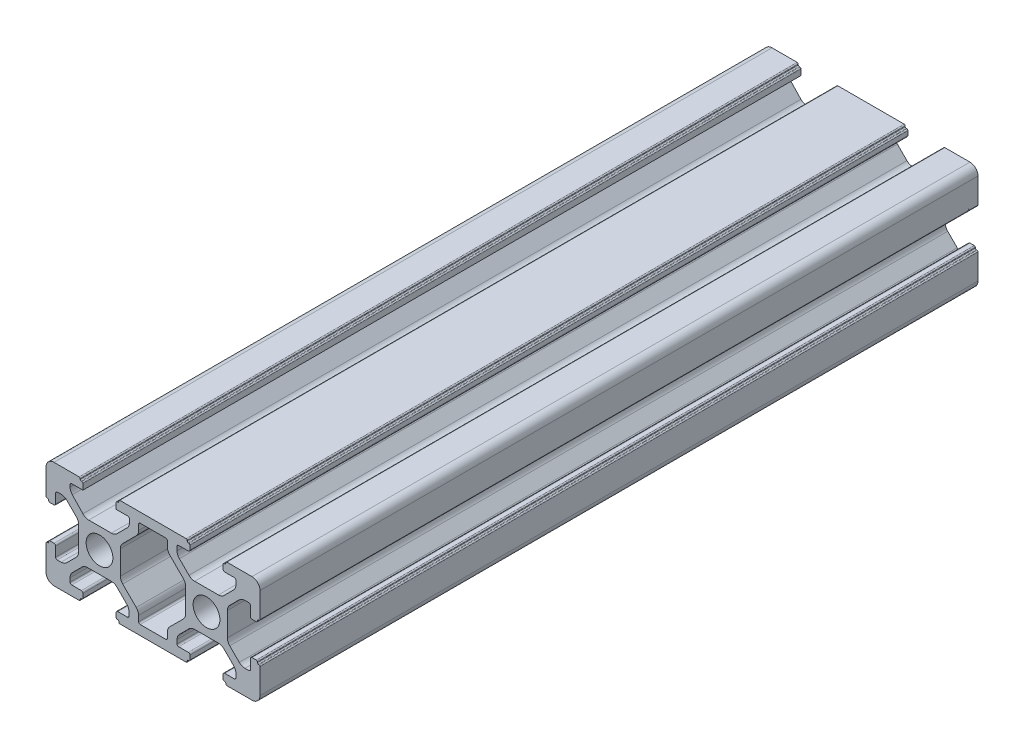
SolidWorks part; units mm, degrees
material "6063-O"
ref_plane "Front Plane" through (0, 0, 0) normal (0, 0, 1) x (1, 0, 0)
ref_plane "Top Plane" through (0, 0, 0) normal (0, 1, 0) x (1, 0, 0)
ref_plane "Right Plane" through (0, 0, 0) normal (1, 0, 0) x (0, 0, -1)
sketch "Sketch1" plane through (0, 0, 0) normal (0, 0, 1) x (1, 0, 0)
  line L0 (1.5, 0) -> (6.2, 0)
  line L1 (40, 1.5) -> (40, 6.2)
  line L2 (38.5, 20) -> (33.8, 20)
  line L3 (0, 18.5) -> (0, 13.8)
  line L4 (17.6, 1.8) -> (22.4, 1.8)
  line L5 (32.218, 13.9) -> (27.782, 13.9)
  line L6 (26.1, 12.218) -> (26.1, 7.782)
  line L7 (17.6, 18.2) -> (22.4, 18.2)
  line L8 (12.218, 13.9) -> (7.9864, 13.9)
  line L9 (6.1, 12.218) -> (6.1, 7.782)
  line L10 (7.782, 6.1) -> (12.218, 6.1)
  line L11 (13.9, 7.782) -> (13.9, 12.218)
  line L12 (27.782, 6.1) -> (32.218, 6.1)
  line L13 (33.9, 7.782) -> (33.9, 12.218)
  line L14 (26.7213, 14.3393) -> (24.9393, 16.1213)
  line L15 (33.2787, 14.3393) -> (35.0607, 16.1213)
  line L16 (34.3393, 13.2787) -> (36.1213, 15.0607)
  line L17 (25.6607, 6.7213) -> (23.1393, 4.2)
  line L18 (15.2, 1.8) -> (13.4, 1.8)
  line L19 (26.7213, 5.6607) -> (24.9393, 3.8787)
  line L20 (24.8, 1.8) -> (26.6, 1.8)
  line L21 (15.3, 18.2) -> (13.1, 18.2)
  line L22 (13.2787, 14.3393) -> (15.1607, 16.2213)
  line L23 (14.3393, 13.2787) -> (16.8607, 15.8)
  line L24 (5.6607, 6.7213) -> (3.8787, 4.9393)
  line L25 (6.7213, 5.6607) -> (4.9393, 3.8787)
  line L26 (6.897, 14.3689) -> (4.9106, 16.4674)
  line L27 (5.6607, 13.2787) -> (3.8787, 15.0607)
  line L28 (14.3393, 6.7213) -> (16.8607, 4.2)
  line L29 (13.2787, 5.6607) -> (15.0607, 3.8787)
  line L30 (24.8, 18.2) -> (26.6, 18.2)
  line L31 (25.6607, 13.2787) -> (23.1393, 15.8)
  line L32 (34.3393, 6.7213) -> (36.1213, 4.9393)
  line L33 (33.2787, 5.6607) -> (35.0607, 3.8787)
  line L34 (1.8, 15.2) -> (1.8, 13.4)
  line L35 (24.5, 2.1) -> (24.5, 2.818)
  line L36 (4.5, 2.1) -> (4.5, 2.818)
  line L37 (2.818, 4.5) -> (2.1, 4.5)
  line L38 (4.5, 17.9) -> (4.5, 17.4986)
  line L39 (2.818, 15.5) -> (2.1, 15.5)
  line L40 (15.6, 17.9) -> (15.6, 17.282)
  line L41 (15.5, 2.818) -> (15.5, 2.1)
  line L42 (38.2, 15.2) -> (38.2, 13.4)
  line L43 (35.5, 2.818) -> (35.5, 2.1)
  line L44 (37.182, 4.5) -> (37.9, 4.5)
  line L45 (35.5, 17.182) -> (35.5, 17.9)
  line L46 (37.182, 15.5) -> (37.9, 15.5)
  line L47 (17.3, 2.1) -> (17.3, 3.1393)
  line L48 (22.7, 2.1) -> (22.7, 3.1393)
  line L49 (17.3, 17.9) -> (17.3, 16.8607)
  line L50 (22.7, 17.9) -> (22.7, 16.8607)
  line L51 (24.5, 17.9) -> (24.5, 17.182)
  line L52 (6.9, 19.3) -> (6.9, 18.2)
  line L53 (13.1, 19.3) -> (13.1, 18.2)
  line L54 (6.9, 1.5) -> (6.9, 0.7)
  line L55 (13.1, 1.5) -> (13.1, 0.7)
  line L56 (13.8, 0) -> (26.2, 0)
  line L57 (6.6, 1.8) -> (4.8, 1.8)
  line L58 (6.9, 18.2) -> (4.8, 18.2)
  line L59 (6.2, 20) -> (1.5, 20)
  line L60 (39.3, 6.9) -> (38.5, 6.9)
  line L61 (39.3, 13.1) -> (38.5, 13.1)
  line L62 (1.5, 13.1) -> (0.7, 13.1)
  line L63 (1.5, 6.9) -> (0.7, 6.9)
  line L64 (0, 6.2) -> (0, 1.5)
  line L65 (1.8, 6.6) -> (1.8, 4.8)
  line L66 (38.2, 6.6) -> (38.2, 4.8)
  line L67 (40, 13.8) -> (40, 18.5)
  line L68 (33.1, 19.3) -> (33.1, 18.5)
  line L69 (26.9, 19.3) -> (26.9, 18.5)
  line L70 (26.9, 1.5) -> (26.9, 0.7)
  line L71 (33.1, 1.5) -> (33.1, 0.7)
  line L72 (33.8, 0) -> (38.5, 0)
  line L73 (33.4, 1.8) -> (35.2, 1.8)
  line L74 (26.2, 20) -> (13.8, 20)
  line L75 (33.4, 18.2) -> (35.2, 18.2)
  line L76 (6.7, 0.5) -> (6.6, 0.5)
  line L77 (6.4, 0.3) -> (6.4, 0.2)
  line L78 (13.3, 0.5) -> (13.4, 0.5)
  line L79 (13.6, 0.3) -> (13.6, 0.2)
  line L80 (26.7, 0.5) -> (26.6, 0.5)
  line L81 (26.4, 0.3) -> (26.4, 0.2)
  line L82 (33.3, 0.5) -> (33.4, 0.5)
  line L83 (33.6, 0.3) -> (33.6, 0.2)
  line L85 (6.4, 19.8) -> (6.4, 19.7)
  line L86 (6.6, 19.5) -> (6.7, 19.5)
  line L87 (13.6, 19.8) -> (13.6, 19.7)
  line L88 (13.4, 19.5) -> (13.3, 19.5)
  line L89 (26.4, 19.8) -> (26.4, 19.7)
  line L90 (26.6, 19.5) -> (26.7, 19.5)
  line L91 (33.6, 19.8) -> (33.6, 19.7)
  line L92 (33.4, 19.5) -> (33.3, 19.5)
  line L93 (0.5, 13.3) -> (0.5, 13.4)
  line L94 (0.3, 13.6) -> (0.2, 13.6)
  line L95 (0.5, 6.7) -> (0.5, 6.6)
  line L96 (0.3, 6.4) -> (0.2, 6.4)
  line L97 (39.5, 13.3) -> (39.5, 13.4)
  line L98 (39.7, 13.6) -> (39.8, 13.6)
  line L99 (39.5, 6.7) -> (39.5, 6.6)
  line L100 (39.7, 6.4) -> (39.8, 6.4)
  circle A0 centre (10, 10) radius 2.5
  circle A1 centre (30, 10) radius 2.5
  arc A2 (38.5, 0) -> (40, 1.5) centre (38.5, 1.5) ccw
  arc A3 (40, 18.5) -> (38.5, 20) centre (38.5, 18.5) ccw
  arc A4 (1.5, 0) -> (0, 1.5) centre (1.5, 1.5) cw
  arc A5 (1.5, 20) -> (0, 18.5) centre (1.5, 18.5) ccw
  arc A6 (26.7213, 5.6607) -> (27.782, 6.1) centre (27.782, 4.6) cw
  arc A7 (32.218, 6.1) -> (33.2787, 5.6607) centre (32.218, 4.6) cw
  arc A8 (33.9, 7.782) -> (34.3393, 6.7213) centre (35.4, 7.782) ccw
  arc A9 (33.2787, 14.3393) -> (32.218, 13.9) centre (32.218, 15.4) cw
  arc A10 (14.3393, 6.7213) -> (13.9, 7.782) centre (15.4, 7.782) cw
  arc A11 (14.3393, 13.2787) -> (13.9, 12.218) centre (15.4, 12.218) ccw
  arc A12 (25.6607, 6.7213) -> (26.1, 7.782) centre (24.6, 7.782) ccw
  arc A13 (26.1, 12.218) -> (25.6607, 13.2787) centre (24.6, 12.218) ccw
  arc A14 (27.782, 13.9) -> (26.7213, 14.3393) centre (27.782, 15.4) cw
  arc A15 (5.6607, 13.2787) -> (6.1, 12.218) centre (4.6, 12.218) cw
  arc A16 (5.6607, 6.7213) -> (6.1, 7.782) centre (4.6, 7.782) ccw
  arc A17 (13.2787, 5.6607) -> (12.218, 6.1) centre (12.218, 4.6) ccw
  arc A18 (6.7213, 5.6607) -> (7.782, 6.1) centre (7.782, 4.6) cw
  arc A19 (13.2787, 14.3393) -> (12.218, 13.9) centre (12.218, 15.4) cw
  arc A20 (6.897, 14.3689) -> (7.9864, 13.9) centre (7.9864, 15.4) ccw
  arc A21 (36.1213, 4.9393) -> (37.182, 4.5) centre (37.182, 6) ccw
  arc A22 (36.1213, 15.0607) -> (37.182, 15.5) centre (37.182, 14) cw
  arc A23 (35.0607, 16.1213) -> (35.5, 17.182) centre (34, 17.182) ccw
  arc A24 (24.5, 17.182) -> (24.9393, 16.1213) centre (26, 17.182) ccw
  arc A25 (22.7, 16.8607) -> (23.1393, 15.8) centre (24.2, 16.8607) ccw
  arc A26 (17.3, 16.8607) -> (16.8607, 15.8) centre (15.8, 16.8607) cw
  arc A27 (4.9106, 16.4674) -> (4.5, 17.4986) centre (6, 17.4986) cw
  arc A28 (15.6, 17.282) -> (15.1607, 16.2213) centre (14.1, 17.282) cw
  arc A29 (3.8787, 15.0607) -> (2.818, 15.5) centre (2.818, 14) ccw
  arc A30 (3.8787, 4.9393) -> (2.818, 4.5) centre (2.818, 6) cw
  arc A31 (4.9393, 3.8787) -> (4.5, 2.818) centre (6, 2.818) ccw
  arc A32 (35.0607, 3.8787) -> (35.5, 2.818) centre (34, 2.818) cw
  arc A33 (24.9393, 3.8787) -> (24.5, 2.818) centre (26, 2.818) ccw
  arc A34 (22.7, 3.1393) -> (23.1393, 4.2) centre (24.2, 3.1393) cw
  arc A35 (17.3, 3.1393) -> (16.8607, 4.2) centre (15.8, 3.1393) ccw
  arc A36 (15.5, 2.818) -> (15.0607, 3.8787) centre (14, 2.818) ccw
  arc A37 (1.8, 6.6) -> (1.5, 6.9) centre (1.5, 6.6) ccw
  arc A38 (1.8, 13.4) -> (1.5, 13.1) centre (1.5, 13.4) cw
  arc A39 (17.6, 18.2) -> (17.3, 17.9) centre (17.6, 17.9) ccw
  arc A40 (22.4, 1.8) -> (22.7, 2.1) centre (22.4, 2.1) ccw
  arc A41 (17.6, 1.8) -> (17.3, 2.1) centre (17.6, 2.1) cw
  arc A42 (15.2, 1.8) -> (15.5, 2.1) centre (15.2, 2.1) ccw
  arc A43 (6.6, 1.8) -> (6.9, 1.5) centre (6.6, 1.5) cw
  arc A44 (13.4, 1.8) -> (13.1, 1.5) centre (13.4, 1.5) ccw
  arc A45 (24.8, 1.8) -> (24.5, 2.1) centre (24.8, 2.1) cw
  arc A46 (35.2, 1.8) -> (35.5, 2.1) centre (35.2, 2.1) ccw
  arc A47 (26.6, 1.8) -> (26.9, 1.5) centre (26.6, 1.5) cw
  arc A48 (33.4, 1.8) -> (33.1, 1.5) centre (33.4, 1.5) ccw
  arc A49 (26.9, 18.5) -> (26.6, 18.2) centre (26.6, 18.5) cw
  arc A50 (33.1, 18.5) -> (33.4, 18.2) centre (33.4, 18.5) ccw
  arc A51 (37.9, 4.5) -> (38.2, 4.8) centre (37.9, 4.8) ccw
  arc A52 (38.5, 13.1) -> (38.2, 13.4) centre (38.5, 13.4) cw
  arc A53 (38.5, 6.9) -> (38.2, 6.6) centre (38.5, 6.6) ccw
  arc A54 (38.2, 15.2) -> (37.9, 15.5) centre (37.9, 15.2) ccw
  arc A55 (35.2, 18.2) -> (35.5, 17.9) centre (35.2, 17.9) cw
  arc A56 (24.8, 18.2) -> (24.5, 17.9) centre (24.8, 17.9) ccw
  arc A57 (22.4, 18.2) -> (22.7, 17.9) centre (22.4, 17.9) cw
  arc A58 (15.3, 18.2) -> (15.6, 17.9) centre (15.3, 17.9) cw
  arc A59 (4.5, 17.9) -> (4.8, 18.2) centre (4.8, 17.9) cw
  arc A60 (1.8, 15.2) -> (2.1, 15.5) centre (2.1, 15.2) cw
  arc A61 (1.8, 4.8) -> (2.1, 4.5) centre (2.1, 4.8) ccw
  arc A62 (4.5, 2.1) -> (4.8, 1.8) centre (4.8, 2.1) ccw
  arc A63 (34.3393, 13.2787) -> (33.9, 12.218) centre (35.4, 12.218) ccw
  arc A64 (6.4, 0.2) -> (6.2, 0) centre (6.2, 0.2) cw
  arc A65 (6.6, 0.5) -> (6.4, 0.3) centre (6.6, 0.3) ccw
  arc A66 (6.7, 0.5) -> (6.9, 0.7) centre (6.7, 0.7) ccw
  arc A67 (13.6, 0.2) -> (13.8, 0) centre (13.8, 0.2) ccw
  arc A68 (13.4, 0.5) -> (13.6, 0.3) centre (13.4, 0.3) cw
  arc A69 (13.3, 0.5) -> (13.1, 0.7) centre (13.3, 0.7) cw
  arc A70 (26.4, 0.2) -> (26.2, 0) centre (26.2, 0.2) cw
  arc A71 (26.6, 0.5) -> (26.4, 0.3) centre (26.6, 0.3) ccw
  arc A72 (26.7, 0.5) -> (26.9, 0.7) centre (26.7, 0.7) ccw
  arc A73 (33.6, 0.2) -> (33.8, 0) centre (33.8, 0.2) ccw
  arc A74 (33.4, 0.5) -> (33.6, 0.3) centre (33.4, 0.3) cw
  arc A75 (33.3, 0.5) -> (33.1, 0.7) centre (33.3, 0.7) cw
  arc A76 (39.8, 6.4) -> (40, 6.2) centre (39.8, 6.2) cw
  arc A77 (39.5, 6.6) -> (39.7, 6.4) centre (39.7, 6.6) ccw
  arc A78 (39.5, 6.7) -> (39.3, 6.9) centre (39.3, 6.7) ccw
  arc A79 (39.5, 13.3) -> (39.3, 13.1) centre (39.3, 13.3) cw
  arc A80 (39.5, 13.4) -> (39.7, 13.6) centre (39.7, 13.4) cw
  arc A81 (39.8, 13.6) -> (40, 13.8) centre (39.8, 13.8) ccw
  arc A82 (33.3, 19.5) -> (33.1, 19.3) centre (33.3, 19.3) ccw
  arc A83 (33.6, 19.7) -> (33.4, 19.5) centre (33.4, 19.7) cw
  arc A84 (33.6, 19.8) -> (33.8, 20) centre (33.8, 19.8) cw
  arc A85 (26.7, 19.5) -> (26.9, 19.3) centre (26.7, 19.3) cw
  arc A86 (26.4, 19.7) -> (26.6, 19.5) centre (26.6, 19.7) ccw
  arc A87 (26.4, 19.8) -> (26.2, 20) centre (26.2, 19.8) ccw
  arc A88 (0.2, 6.4) -> (0, 6.2) centre (0.2, 6.2) ccw
  arc A89 (0.5, 6.6) -> (0.3, 6.4) centre (0.3, 6.6) cw
  arc A90 (0.5, 6.7) -> (0.7, 6.9) centre (0.7, 6.7) cw
  arc A91 (13.3, 19.5) -> (13.1, 19.3) centre (13.3, 19.3) ccw
  arc A92 (13.6, 19.7) -> (13.4, 19.5) centre (13.4, 19.7) cw
  arc A93 (13.6, 19.8) -> (13.8, 20) centre (13.8, 19.8) cw
  arc A94 (6.2, 20) -> (6.4, 19.8) centre (6.2, 19.8) cw
  arc A95 (6.7, 19.5) -> (6.9, 19.3) centre (6.7, 19.3) cw
  arc A96 (6.4, 19.7) -> (6.6, 19.5) centre (6.6, 19.7) ccw
  arc A97 (0.5, 13.3) -> (0.7, 13.1) centre (0.7, 13.3) ccw
  arc A98 (0.2, 13.6) -> (0, 13.8) centre (0.2, 13.8) cw
  arc A99 (0.5, 13.4) -> (0.3, 13.6) centre (0.3, 13.4) ccw
  point P87 (0, 0)
  point P178 (1.8, 6.9)
  point P181 (1.8, 13.1)
  point P186 (22.7, 1.8)
  point P193 (6.9, 1.8)
  point P204 (33.1, 1.8)
  point P209 (33.1, 18.2)
  point P216 (38.2, 6.9)
  point P243 (6.9, 0.5)
  point P248 (13.6, 0.5)
  point P257 (26.9, 0.5)
extrude "Boss-Extrude2" add sketch "Sketch1" along normal blind 134.2 contours A57 L7 A39 L49 A26 L23 A11 L11 A10 L28 A35 L47 A41 L4 A40 L48 A34 L17 A12 L6 A13 L31 A25 L50 | A0 | A1 | L59 A5 L3 A98 L94 A99 L93 A97 L62 A38 L34 A60 L39 A29 L27 A15 L9 A16 L24 A30 L37 A61 L65 A37 L63 A90 L95 A89 L96 A88 L64 A4 L0 A64 L77 A65 L76 A66 L54 A43 L57 A62 L36 A31 L25 A18 L10 A17 L29 A36 L41 A42 L18 A44 L55 A69 L78 A68 L79 A67 L56 A70 L81 A71 L80 A72 L70 A47 L20 A45 L35 A33 L19 A6 L12 A7 L33 A32 L43 A46 L73 A48 L71 A75 L82 A74 L83 A73 L72 A2 L1 A76 L100 A77 L99 A78 L60 A53 L66 A51 L44 A21 L32 A8 L13 A63 L16 A22 L46 A54 L42 A52 L61 A79 L97 A80 L98 A81 L67 A3 L2 A84 L91 A83 L92 A82 L68 A50 L75 A55 L45 A23 L15 A9 L5 A14 L14 A24 L51 A56 L30 A49 L69 A85 L90 A86 L89 A87 L74 A93 L87 A92 L88 A91 L53 L21 A58 L40 A28 L22 A19 L8 A20 L26 A27 L38 A59 L58 L52 A95 L86 A96 L85 A94
